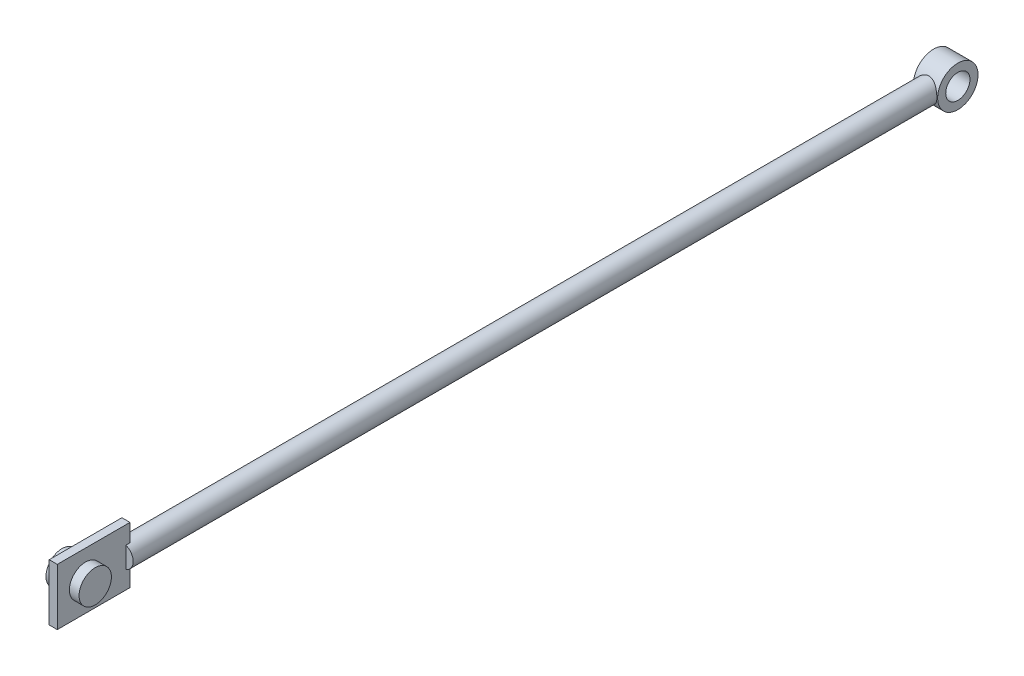
SolidWorks part; units mm, degrees
ref_plane "Front Plane" through (0, 0, 0) normal (0, 0, 1) x (1, 0, 0)
ref_plane "Top Plane" through (0, 0, 0) normal (0, 1, 0) x (1, 0, 0)
ref_plane "Right Plane" through (0, 0, 0) normal (1, 0, 0) x (0, 0, -1)
sketch "Sketch1" plane through (0, 0, 0) normal (0, 0, 1) x (1, 0, 0)
  circle A0 centre (0, 0) radius 1.4
  dimension "D1" = 2.8
extrude "Boss-Extrude1" add sketch "Sketch1" along normal blind 100
sketch "Sketch2" plane through (0, 0, 0) normal (0, 1, 0) x (1, 0, 0)
  line L0 (1.4, 0) -> (-1.4, 0) construction
  line L1 (-1.5, 0.5) -> (1.5, 0.5)
  line L2 (-1.5, 0.5) -> (-1.5, -0.5)
  line L3 (-1.5, -0.5) -> (1.5, -0.5)
  line L4 (1.5, 0.5) -> (1.5, -0.5)
  line L5 (1.4, 0) -> (-1.4, 0) construction
  line L6 (-2.4426, 2) -> (2.1134, 2) construction
  dimension "D1" = 1
  dimension "D2" = 3
  dimension "D3" = 1.5
  dimension "D4" = 2
  dimension "D5" = 2.5
revolve "Revolve1" add sketch "Sketch2" angle 360 about L6
ref_plane "Plane1" through (0, 0, 99.5) normal (0, 0, 1) x (1, 0, 0)
sketch "Sketch3" plane through (0, 0, 99.5) normal (0, 0, 1) x (1, 0, 0)
  line L1 (-0.5, 3.5) -> (0.5, 3.5)
  line L2 (-0.5, 3.5) -> (-0.5, -3.5)
  line L3 (-0.5, -3.5) -> (0.5, -3.5)
  line L4 (0.5, 3.5) -> (0.5, -3.5)
  dimension "D1" = 3.5
  dimension "D2" = 1
  dimension "D3" = 0.5
  dimension "D4" = 7
extrude "Boss-Extrude2" add sketch "Sketch3" along normal blind 9
sketch "Sketch4" plane through (0, 0, 0) normal (1, 0, 0) x (0, 0, -1)
  line L0 (-108.5, -3.5) -> (-108.5, 3.5) construction
  circle A0 centre (-105, 0) radius 2
  point P4 (0, 0)
  dimension "D2" = 4
  dimension "D1" = 3.5
extrude "Boss-Extrude3" add sketch "Sketch4" along normal blind 1.7 and the other way blind 2.4
